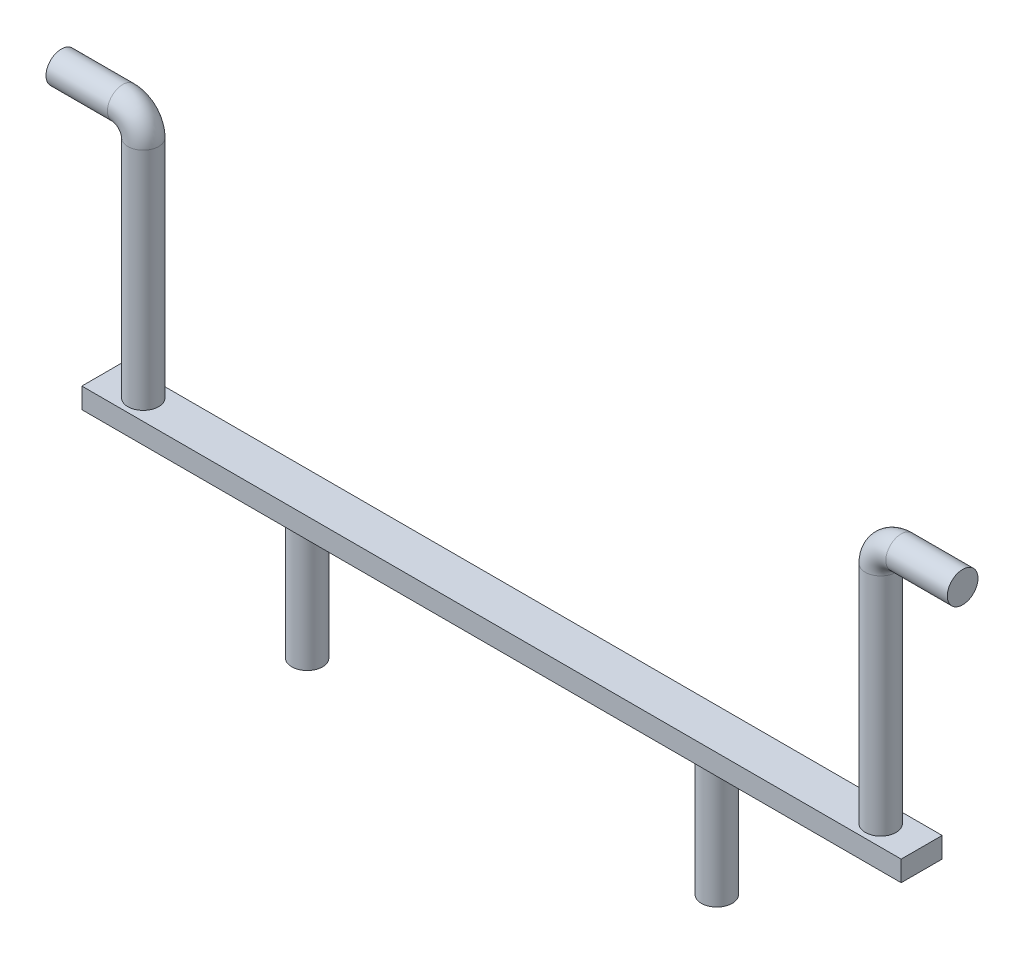
SolidWorks part; units mm, degrees
ref_plane "Front Plane" through (0, 0, 0) normal (0, 0, 1) x (1, 0, 0)
ref_plane "Top Plane" through (0, 0, 0) normal (0, 1, 0) x (1, 0, 0)
ref_plane "Right Plane" through (0, 0, 0) normal (1, 0, 0) x (0, 0, -1)
sketch "Sketch1" plane through (0, 0, 0) normal (0, 1, 0) x (1, 0, 0)
  line L1 (-254, 12.7) -> (254, 12.7)
  line L2 (-254, 12.7) -> (-254, -12.7)
  line L3 (-254, -12.7) -> (254, -12.7)
  line L4 (254, 12.7) -> (254, -12.7)
  line L5 (-254, 12.7) -> (254, -12.7) construction
  line L6 (-254, -12.7) -> (254, 12.7) construction
  point P0 (0, 0)
  dimension "D1" = 508
  dimension "D2" = 25.4
extrude "Boss-Extrude1" add sketch "Sketch1" along normal blind 12.7
sketch "Sketch2" plane through (0, 12.7, 0) normal (0, 1, 0) x (1, 0, 0)
  line L0 (254, 12.7) -> (-254, 12.7) construction
  line L1 (0, 0) -> (0, 166.3935) construction
  line L2 (-254, 12.7) -> (-254, -12.7) construction
  circle A0 centre (-228.6, 0) radius 9.525
  circle A1 centre (228.6, 0) radius 9.525
  dimension "D1" = 25.4
  dimension "D2" = 19.05
  dimension "D3" = 12.7
sketch "Sketch3" plane through (0, 0, 0) normal (0, -1, 0) x (1, 0, 0)
  line L0 (0, 0) -> (0, 189.5094) construction
  line L1 (-254, 12.7) -> (254, 12.7) construction
  circle A0 centre (-127, 0) radius 9.525
  circle A1 centre (127, 0) radius 9.525
  dimension "D1" = 19.05
  dimension "D2" = 12.7
  dimension "D3" = 127
extrude "Boss-Extrude2" add sketch "Sketch3" along normal blind 76.2
sketch "Sketch4" plane through (0, 0, 0) normal (0, 0, 1) x (1, 0, 0)
  line L0 (-228.6, 12.7) -> (-228.6, 152.4)
  line L1 (-241.3, 165.1) -> (-279.4, 165.1)
  line L2 (0, 0) -> (0, 177.8686) construction
  arc A0 (-228.6, 152.4) -> (-241.3, 165.1) centre (-241.3, 152.4) ccw
  point P6 (-228.6, 165.1)
  dimension "D3" = 12.7
  dimension "D1" = 152.4
  dimension "D2" = 50.8
sweep "Sweep1" add path "Sketch4" circular profile diameter 19.05 parameters "D3"=19.05
mirror "Mirror1" about plane through (0, 0, 0) normal (1, 0, 0) of "Sweep1"
